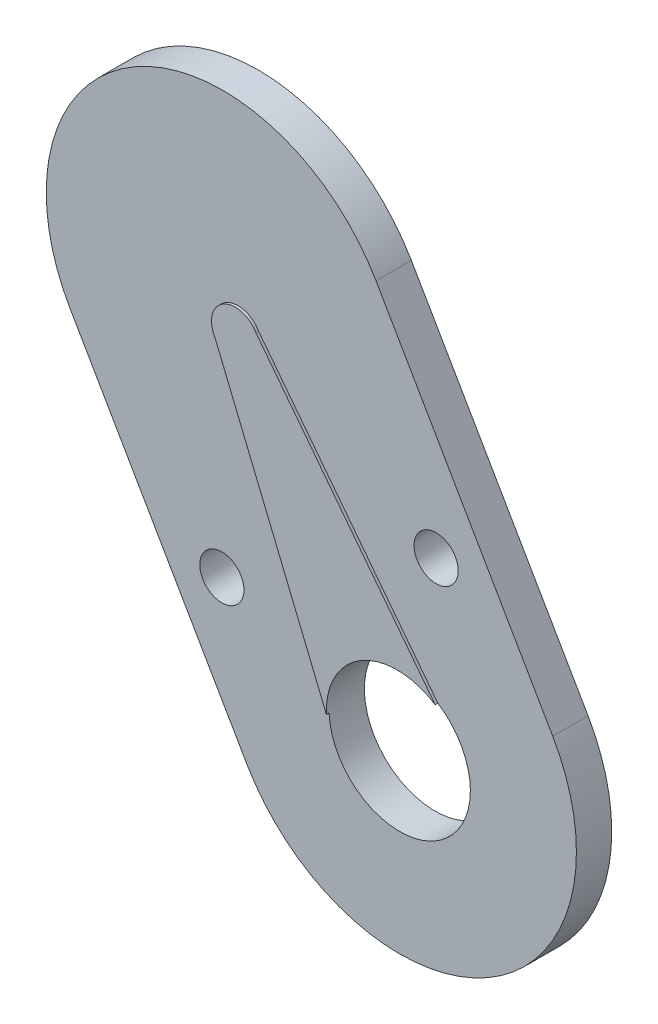
SolidWorks part; units mm, degrees
ref_plane "前视基准面" through (0, 0, 0) normal (0, 0, 1) x (1, 0, 0)
ref_plane "上视基准面" through (0, 0, 0) normal (0, 1, 0) x (1, 0, 0)
ref_plane "右视基准面" through (0, 0, 0) normal (1, 0, 0) x (0, 0, -1)
other "Configuration Table"
sketch "草图1" plane through (0, 0, 0) normal (0, 0, 1) x (1, 0, 0)
  line L0 (8.6603, 5) -> (-1.3397, 22.3205)
  line L1 (-1.3397, 22.3205) -> (-18.6603, 12.3205)
  line L2 (-18.6603, 12.3205) -> (-8.6603, -5)
  line L3 (-8.6603, -5) -> (8.6603, 5)
extrude "Retainer_plate_2mm" add sketch "草图1" along normal blind 2 from offset 2
sketch "草图2" plane through (0, 0, 0) normal (0, 0, 1) x (1, 0, 0)
  circle A0 centre (0, 0) radius 10
extrude "Retainer_plate_2mm_root" add sketch "草图2" along normal blind 2 from offset 2
sketch "草图3" plane through (0, 0, 0) normal (0, 0, 1) x (1, 0, 0)
  circle A0 centre (-10, 17.3205) radius 10
extrude "Retainer_plate_2mm_tip" add sketch "草图3" along normal blind 2 from offset 2
sketch "草图4" plane through (0, 0, 0) normal (0, 0, 1) x (1, 0, 0)
  line L0 (3.2909, 1.9) -> (-7.9809, 16.5233)
  line L1 (-7.9809, 16.5233) -> (-10.3191, 15.1733)
  line L2 (-10.3191, 15.1733) -> (-3.2909, -1.9)
  line L3 (-3.2909, -1.9) -> (3.2909, 1.9)
extrude "Horn_contact_pad_0p15" add sketch "草图4" along normal blind 0.15 from offset 0
sketch "草图5" plane through (0, 0, 0) normal (0, 0, 1) x (1, 0, 0)
  circle A0 centre (0, 0) radius 3.8
extrude "Horn_contact_pad_0p15_root" add sketch "草图5" along normal blind 0.15 from offset 0
sketch "草图6" plane through (0, 0, 0) normal (0, 0, 1) x (1, 0, 0)
  circle A0 centre (-9.15, 15.8483) radius 1.35
extrude "Horn_contact_pad_0p15_tip" add sketch "草图6" along normal blind 0.15 from offset 0
sketch "草图7" plane through (0, 0, 0) normal (0, 0, 1) x (1, 0, 0)
  circle A0 centre (0, 0) radius 4
extrude "Boss_clearance_8" cut sketch "草图7" along normal blind 2.5 from offset 2.1
sketch "草图8" plane through (0, 0, 0) normal (0, 0, 1) x (1, 0, 0)
  circle A0 centre (2.0622, 10.4282) radius 1.25
  circle A1 centre (-10.0622, 3.4282) radius 1.25
extrude "M2_clearance_2p5_pitch14" cut sketch "草图8" along normal blind 2.5 from offset 2.1
